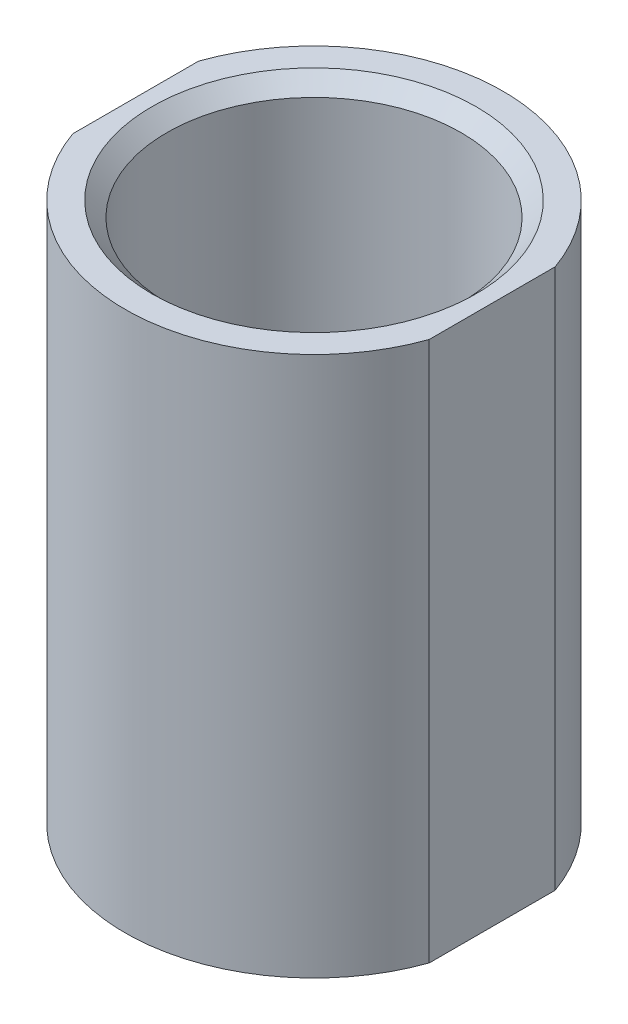
SolidWorks part; units mm, degrees
material "1.4000 (X6Cr13)"
ref_plane "前视基准面" through (0, 0, 0) normal (0, 0, 1) x (1, 0, 0)
ref_plane "上视基准面" through (0, 0, 0) normal (0, 1, 0) x (1, 0, 0)
ref_plane "右视基准面" through (0, 0, 0) normal (1, 0, 0) x (0, 0, -1)
other "Configuration Table"
sketch "草图1" plane through (0, 0, 0) normal (0, 1, 0) x (1, 0, 0)
  line L0 (-33, 11.6619) -> (-33, -11.6619)
  line L1 (0, 0) -> (-35, 0) construction
  line L2 (0, 6.8275) -> (0, -11.6619) construction
  line L3 (33, 11.6619) -> (33, -11.6619)
  circle A0 centre (0, 0) radius 35
  dimension "D1" = 70
  dimension "D2" = 2
extrude "凸台-拉伸2" add sketch "草图1" along normal blind 100 contours L3 A0 L0
sketch "草图4" plane through (0, 100, 0) normal (0, 1, 0) x (1, 0, 0)
  circle A0 centre (0, 0) radius 17.112
hole_wizard "M60 螺纹孔2" positions "3D草图2" profile "草图5" tap size "M60" standard "GB" end condition through all
sketch3d "3D草图2"
  point P0 (0, 100, 0)
sketch "草图5" plane through (0, 100, 0) normal (1, 0, 0) x (0, 0, 1)
  line L0 (0, 0) -> (0, 100)
  line L1 (0, 100) -> (27.25, 100)
  line L2 (27.25, 100) -> (27.25, 2.775)
  line L3 (27.25, 2.775) -> (30.025, 0)
  line L5 (30.025, 0) -> (0, 0)
  line L6 (-27.25, 2.775) -> (-30.025, 0) construction
  line L11 (0, -6.35) -> (0, 107.95) construction
  dimension "通孔螺纹孔钻头直径" = 54.5
  dimension "通孔螺纹孔钻头深度" = 100
  dimension "近端锥形沉头孔直径" = 60.05
  dimension "近端锥形沉头孔角度" = 90
cosmetic thread "孔螺蚊线3" parameters "D2"=60
